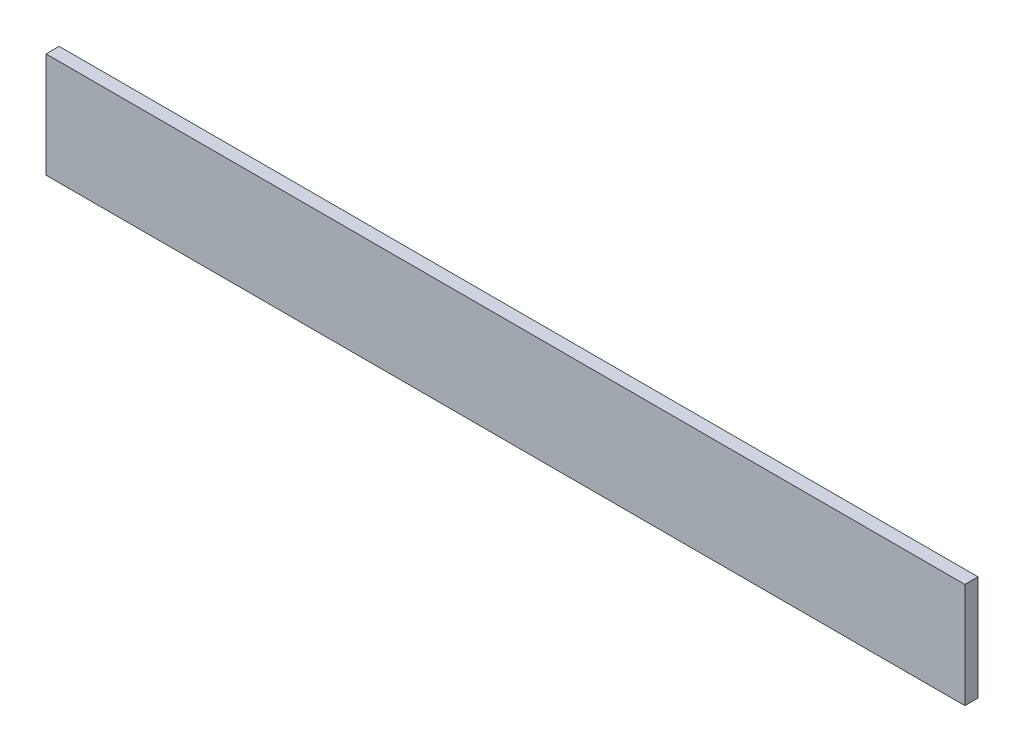
SolidWorks part; units mm, degrees
ref_plane "前视基准面" through (0, 0, 0) normal (0, 0, 1) x (1, 0, 0)
ref_plane "上视基准面" through (0, 0, 0) normal (0, 1, 0) x (1, 0, 0)
ref_plane "右视基准面" through (0, 0, 0) normal (1, 0, 0) x (0, 0, -1)
sketch "草图1" plane through (0, 0, 0) normal (0, 0, 1) x (1, 0, 0)
  line L1 (-175, 20) -> (175, 20)
  line L2 (-175, 20) -> (-175, -20)
  line L3 (-175, -20) -> (175, -20)
  line L4 (175, 20) -> (175, -20)
  line L5 (0, -20) -> (0, 20) construction
  line L6 (-175, 0) -> (175, 0) construction
  point P0 (0, 0)
  dimension "D1" = 40
  dimension "D2" = 350
extrude "凸台-拉伸1" add sketch "草图1" along normal blind 5
